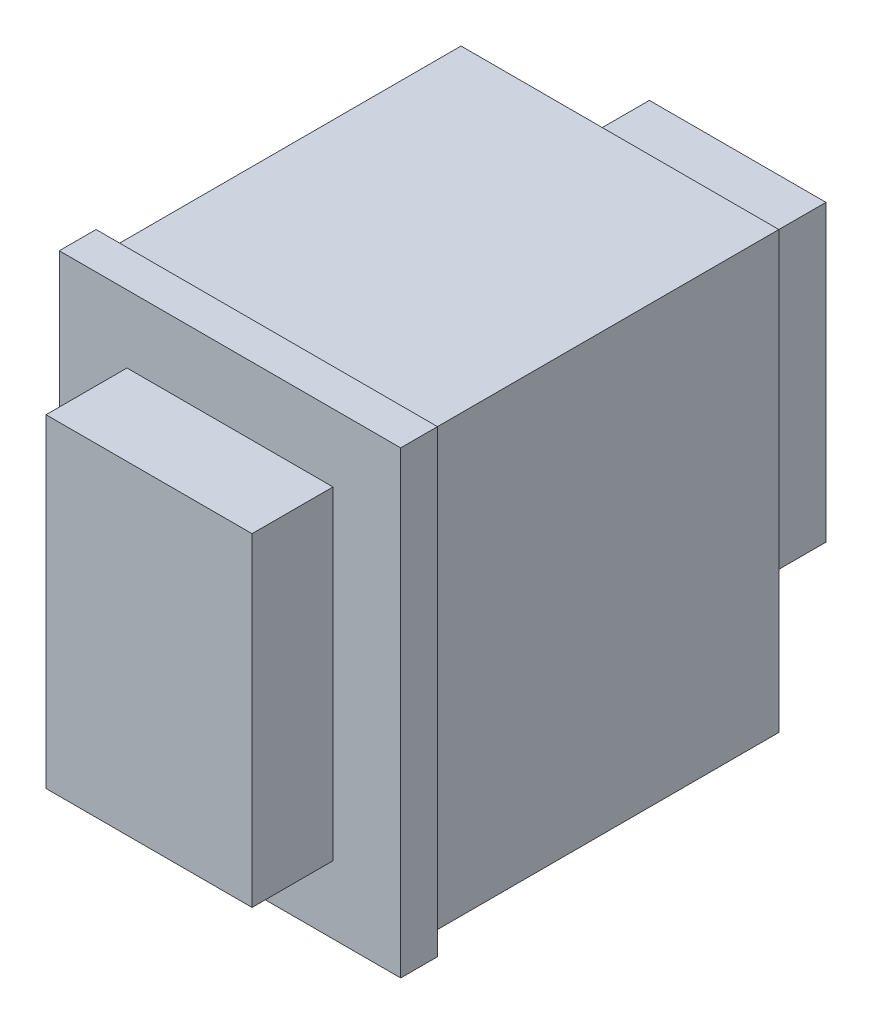
SolidWorks part; units mm, degrees
ref_plane "Front Plane" through (0, 0, 0) normal (0, 0, 1) x (1, 0, 0)
ref_plane "Top Plane" through (0, 0, 0) normal (0, 1, 0) x (1, 0, 0)
ref_plane "Right Plane" through (0, 0, 0) normal (1, 0, 0) x (0, 0, -1)
sketch "Sketch1" plane through (0, 0, 0) normal (0, 0, 1) x (1, 0, 0)
  line L0 (-11.6, -15.6) -> (11.6, -15.6)
  line L1 (11.6, -15.6) -> (11.6, 15.6)
  line L2 (11.6, 15.6) -> (-11.6, 15.6)
  line L3 (-11.6, 15.6) -> (-11.6, -15.6)
extrude "Bezel" add sketch "Sketch1" along normal blind 2.5
ref_plane "P_Front_2p5" through (0, 0, 2.5) normal (0, 0, 1) x (1, 0, 0)
sketch "Sketch2" plane through (0, 0, 2.5) normal (0, 0, 1) x (1, 0, 0)
  line L0 (-7, -11) -> (7, -11)
  line L1 (7, -11) -> (7, 11)
  line L2 (7, 11) -> (-7, 11)
  line L3 (-7, 11) -> (-7, -11)
extrude "Rocker" add sketch "Sketch2" along normal blind 5.5
ref_plane "P_Front_m24" through (0, 0, -24) normal (0, 0, 1) x (1, 0, 0)
sketch "Sketch3" plane through (0, 0, -24) normal (0, 0, 1) x (1, 0, 0)
  line L0 (-10.8, -14.8) -> (10.8, -14.8)
  line L1 (10.8, -14.8) -> (10.8, 14.8)
  line L2 (10.8, 14.8) -> (-10.8, 14.8)
  line L3 (-10.8, 14.8) -> (-10.8, -14.8)
extrude "Body" add sketch "Sketch3" along normal blind 24
ref_plane "P_Front_m32" through (0, 0, -32) normal (0, 0, 1) x (1, 0, 0)
sketch "Sketch4" plane through (0, 0, -32) normal (0, 0, 1) x (1, 0, 0)
  line L0 (-6, -10) -> (6, -10)
  line L1 (6, -10) -> (6, 10)
  line L2 (6, 10) -> (-6, 10)
  line L3 (-6, 10) -> (-6, -10)
extrude "Terminals" add sketch "Sketch4" along normal blind 8
